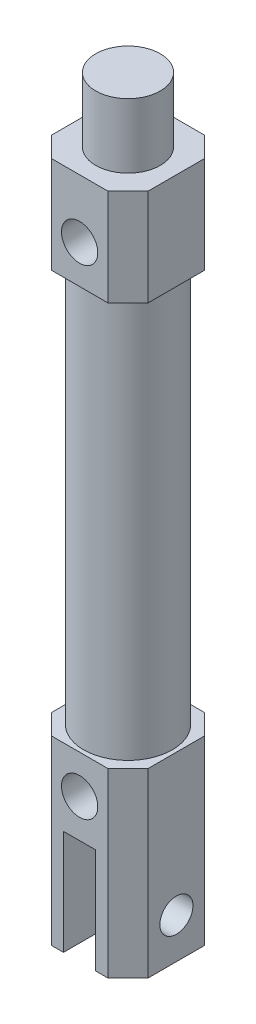
SolidWorks part; units mm, degrees
ref_plane "Front Plane" through (0, 0, 0) normal (0, 0, 1) x (1, 0, 0)
ref_plane "Top Plane" through (0, 0, 0) normal (0, 1, 0) x (1, 0, 0)
ref_plane "Right Plane" through (0, 0, 0) normal (1, 0, 0) x (0, 0, -1)
sketch "Sketch1" plane through (0, 0, 0) normal (0, 1, 0) x (1, 0, 0)
  line L1 (-6, -6) -> (6, -6)
  line L2 (-6, -6) -> (-6, 6)
  line L3 (-6, 6) -> (6, 6)
  line L4 (6, -6) -> (6, 6)
  line L5 (-6, -6) -> (6, 6) construction
  line L6 (-6, 6) -> (6, -6) construction
  point P0 (0, 0)
  dimension "D1" = 12
  dimension "D2" = 12
extrude "Boss-Extrude1" add sketch "Sketch1" along normal blind 22.5
sketch "Sketch2" plane through (0, 22.5, 0) normal (0, 1, 0) x (1, 0, 0)
  circle A0 centre (0, 0) radius 5.5
  dimension "D1" = 11
extrude "Boss-Extrude2" add sketch "Sketch2" along normal blind 50
sketch "Sketch3" plane through (0, 72.5, 0) normal (0, 1, 0) x (1, 0, 0)
  line L1 (-6, 6) -> (6, 6)
  line L2 (-6, 6) -> (-6, -6)
  line L3 (-6, -6) -> (6, -6)
  line L4 (6, 6) -> (6, -6)
  line L5 (-6, 6) -> (6, -6) construction
  line L6 (-6, -6) -> (6, 6) construction
  point P0 (0, 0)
extrude "Boss-Extrude3" add sketch "Sketch3" along normal blind 12
sketch "Sketch4" plane through (0, 84.5, 0) normal (0, 1, 0) x (1, 0, 0)
  circle A0 centre (0, 0) radius 4
  dimension "D1" = 8
extrude "Boss-Extrude4" add sketch "Sketch4" along normal blind 8
chamfer "Chamfer1" distance 2.5 angle 45 4 edges at (-6, 11.25, 6) (-6, 11.25, -6) (6, 11.25, -6) (6, 11.25, 6)
chamfer "Chamfer2" distance 2.5 angle 45 4 edges at (-6, 78.5, -6) (-6, 78.5, 6) (6, 78.5, 6) (6, 78.5, -6)
sketch "Sketch5" plane through (0, 0, 6) normal (0, 0, 1) x (1, 0, 0)
  line L0 (-3.5, 0) -> (3.5, 0) construction
  line L1 (-2, 0) -> (2, 0)
  line L2 (-2, 0) -> (-2, 13)
  line L3 (-2, 13) -> (2, 13)
  line L4 (2, 0) -> (2, 13)
  point P6 (0, 13)
  dimension "D1" = 4
  dimension "D2" = 13
extrude "Cut-Extrude1" cut sketch "Sketch5" against normal through all
sketch "Sketch6" plane through (6, 0, 0) normal (1, 0, 0) x (0, 0, -1)
  circle A0 centre (0, 5) radius 2.05
  point P2 (0, 0)
  point P4 (0, 9.7868)
  dimension "D1" = 4.1
  dimension "D2" = 5
extrude "Cut-Extrude2" cut sketch "Sketch6" against normal through all
sketch "Sketch7" plane through (0, 0, 6) normal (0, 0, 1) x (1, 0, 0)
  line L0 (2, 13) -> (-2, 13) construction
  circle A0 centre (0, 17.75) radius 2.25
  point P4 (0, 0)
  dimension "D1" = 4.75
  dimension "D2" = 4.5
extrude "Cut-Extrude3" cut sketch "Sketch7" against normal blind 7
sketch "Sketch8" plane through (0, 0, 6) normal (0, 0, 1) x (1, 0, 0)
  line L0 (-3.5, 72.5) -> (3.5, 72.5) construction
  circle A0 centre (0, 77.25) radius 2.25
  point P4 (0, 0)
  dimension "D1" = 4.75
  dimension "D2" = 4.5
extrude "Cut-Extrude4" cut sketch "Sketch8" against normal blind 7
